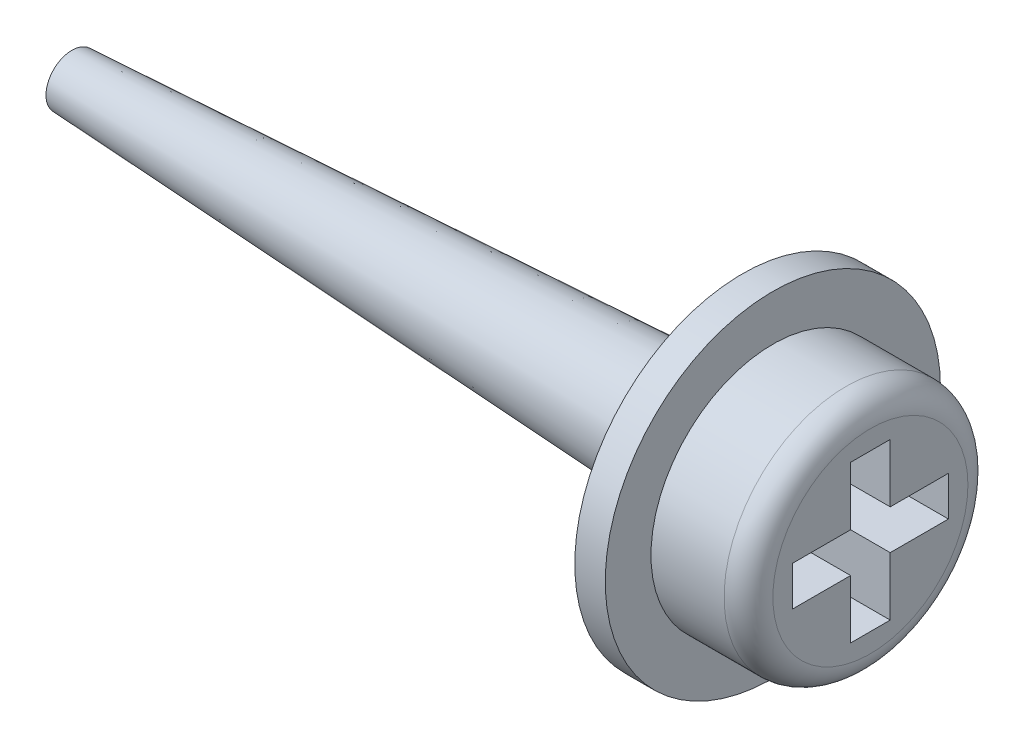
SolidWorks part; units mm, degrees
ref_plane "Plan de face" through (0, 0, 0) normal (0, 0, 1) x (1, 0, 0)
ref_plane "Plan de dessus" through (0, 0, 0) normal (0, 1, 0) x (1, 0, 0)
ref_plane "Plan de droite" through (0, 0, 0) normal (1, 0, 0) x (0, 0, -1)
sketch "Esquisse4" plane through (0, 0, 0) normal (0, 0, 1) x (1, 0, 0)
  line L0 (-3.0182, 0) -> (10.1818, 0) construction
  line L1 (-3.0182, 0.51) -> (10.1818, 1.2)
  line L2 (10.1818, 1.2) -> (10.1818, -1.2)
  line L3 (-3.0182, 0.51) -> (-3.0182, -0.51)
  line L4 (-3.0182, -0.51) -> (10.1818, -1.2)
  dimension "D1" = 1.02
  dimension "D2" = 2.4
  dimension "D3" = 13.2
revolve "Révolution2" add sketch "Esquisse4" angle 360 about L0
sketch "Esquisse5" plane through (10.1818, 0, 0) normal (1, 0, 0) x (0, 0, -1)
  circle A0 centre (0, 0) radius 3.3
  dimension "D1" = 6.6
extrude "Boss.-Extru.3" add sketch "Esquisse5" along normal blind 0.6
sketch "Esquisse6" plane through (10.7818, 0, 0) normal (1, 0, 0) x (0, 0, -1)
  circle A0 centre (0, 0) radius 2.4
  dimension "D1" = 4.8
extrude "Boss.-Extru.4" add sketch "Esquisse6" along normal blind 1.92
sketch "Esquisse7" plane through (12.7018, 0, 0) normal (1, 0, 0) x (0, 0, -1)
  line L0 (-3.713, 0) -> (3.882, 0) construction
  line L1 (0, 3.6219) -> (0, -3.882) construction
  line L2 (-0.39, 1.54) -> (0.39, 1.54)
  line L3 (0.39, 1.54) -> (0.39, 0.39)
  line L4 (0.39, 0.39) -> (1.536, 0.39)
  line L5 (1.536, 0.39) -> (1.536, -0.39)
  line L6 (-1.536, 0.39) -> (-1.536, -0.39)
  line L7 (-0.39, 0.39) -> (-1.536, 0.39)
  line L8 (-0.39, 1.54) -> (-0.39, 0.39)
  line L9 (0.39, -0.39) -> (1.536, -0.39)
  line L10 (0.39, -1.54) -> (0.39, -0.39)
  line L11 (-0.39, -1.54) -> (-0.39, -0.39)
  line L12 (-0.39, -1.54) -> (0.39, -1.54)
  line L13 (-0.39, -0.39) -> (-1.536, -0.39)
  point P13 (0, -1.54)
  point P16 (0, 1.54)
  point P17 (1.536, 0)
  point P22 (-1.536, 0)
  dimension "D2" = 1.536
  dimension "D3" = 1.54
  dimension "D4" = 0.78
  dimension "D5" = 0.78
extrude "Enlèv. mat.-Extru.2" cut sketch "Esquisse7" against normal blind 1.92
fillet "Congé2" radius 0.36 4 edges at (10.7818, -1.54, 0) (10.7818, 0, 1.536) (10.7818, 0, -1.536) (10.7818, 1.54, 0)
fillet "Congé3" radius 0.48 1 edges at (12.7018, 0, -2.4)
